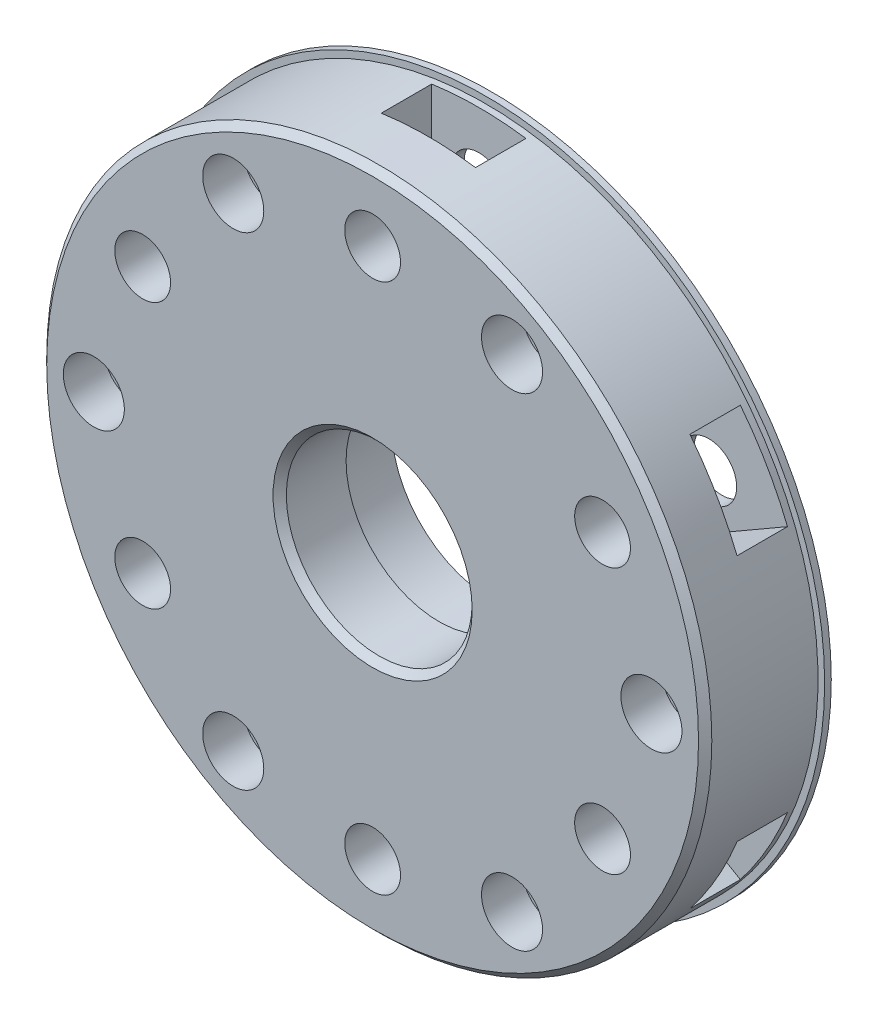
SolidWorks part; units mm, degrees
material "ABS"
ref_plane "Front Plane" through (0, 0, 0) normal (0, 0, 1) x (1, 0, 0)
ref_plane "Top Plane" through (0, 0, 0) normal (0, 1, 0) x (1, 0, 0)
ref_plane "Right Plane" through (0, 0, 0) normal (1, 0, 0) x (0, 0, -1)
sketch "Output Master Sketch" plane through (0, 0, 0) normal (0, 0, 1) x (1, 0, 0)
  circle A0 centre (0, 0) radius 21 construction
  circle A1 centre (21, 0) radius 3.05 construction
  circle A2 centre (10.5, -18.1865) radius 3.05 construction
  circle A3 centre (-10.5, -18.1865) radius 3.05 construction
  circle A4 centre (-21, 0) radius 3.05 construction
  circle A5 centre (-10.5, 18.1865) radius 3.05 construction
  circle A6 centre (10.5, 18.1865) radius 3.05 construction
  circle A7 centre (0, 0) radius 25.05
  point P17 (0, 0)
extrude "Boss-Extrude1" add sketch "Output Master Sketch" along normal blind 9
sketch "Sketch4" plane through (0, 0, 0) normal (0, 0, 1) x (1, 0, 0)
  circle A0 centre (21, 0) radius 3.05
  circle A1 centre (21, 0) radius 3.05 construction
  circle A2 centre (10.5, -18.1865) radius 3.05
  circle A3 centre (-10.5, -18.1865) radius 3.05
  circle A4 centre (-21, 0) radius 3.05
  circle A5 centre (-10.5, 18.1865) radius 3.05
  circle A6 centre (10.5, 18.1865) radius 3.05
  point P17 (0, 0)
  dimension "D1" = 6
extrude "Cut-Extrude1" cut sketch "Sketch4" along normal blind 4
sketch "Sketch5" plane through (0, 0, 0) normal (0, 0, -1) x (-1, 0, 0)
  circle A0 centre (0, 0) radius 25.05
  circle A1 centre (0, 0) radius 25.55
  circle A2 centre (0, 0) radius 25.05 construction
  dimension "D1" = 0.5
extrude "Boss-Extrude2" add sketch "Sketch5" against normal blind 0.5
sketch "Sketch6" plane through (0, 0, 0) normal (0, 0, -1) x (-1, 0, 0)
  circle A0 centre (-21, 0) radius 1.55
  circle A1 centre (-10.5, 18.1865) radius 1.55
  circle A2 centre (10.5, 18.1865) radius 1.55
  circle A3 centre (21, 0) radius 1.55
  circle A4 centre (10.5, -18.1865) radius 1.55
  circle A5 centre (-10.5, -18.1865) radius 1.55
  point P15 (0, 0)
  dimension "D1" = 3.1
  dimension "D2" = 6
extrude "Cut-Extrude2" cut sketch "Sketch6" against normal through all
sketch "Sketch7" plane through (0, 0, 9) normal (0, 0, 1) x (1, 0, 0)
  circle A0 centre (-21, 0) radius 2.3
  circle A1 centre (-10.5, 18.1865) radius 2.3
  circle A2 centre (10.5, 18.1865) radius 2.3
  circle A3 centre (21, 0) radius 2.3
  circle A4 centre (10.5, -18.1865) radius 2.3
  circle A5 centre (-10.5, -18.1865) radius 2.3
  point P16 (0, 0)
  dimension "D1" = 4.6
  dimension "D2" = 6
extrude "Cut-Extrude3" cut sketch "Sketch7" against normal blind 3.1
chamfer "Chamfer1" distance 0.5 angle 45 1 edges at (25.05, 0, 9)
sketch "Sketch8" plane through (0, 0, 0) normal (0, 0, -1) x (-1, 0, 0)
  circle A0 centre (0, 0) radius 7
  dimension "D1" = 14
extrude "Cut-Extrude4" cut sketch "Sketch8" against normal blind 10
sketch "Sketch9" plane through (0, 0, 0) normal (0, 0, -1) x (-1, 0, 0)
  circle A0 centre (0, 0) radius 7.575
  dimension "D1" = 15.15
extrude "Cut-Extrude5" cut sketch "Sketch9" against normal blind 4
sketch "Sketch10" plane through (0, 0, 9) normal (0, 0, 1) x (1, 0, 0)
  line L1 (0, 20) -> (-17.3205, 10) construction
  line L2 (-17.3205, 10) -> (-17.3205, -10) construction
  line L3 (-17.3205, -10) -> (0, -20) construction
  line L4 (0, -20) -> (17.3205, -10) construction
  line L5 (17.3205, -10) -> (17.3205, 10) construction
  line L6 (17.3205, 10) -> (0, 20) construction
  circle A0 centre (0, 0) radius 20 construction
  circle A1 centre (0, 20) radius 2.1
  circle A2 centre (17.3205, 10) radius 2.1
  circle A3 centre (17.3205, -10) radius 2.1
  circle A4 centre (0, -20) radius 2.1
  circle A5 centre (-17.3205, -10) radius 2.1
  circle A6 centre (-17.3205, 10) radius 2.1
  point P22 (0, 0)
  dimension "D1" = 40
  dimension "D2" = 4.2
  dimension "D3" = 6
extrude "M4 Thru" cut sketch "Sketch10" against normal through all
chamfer "Chamfer3" distance 0.5 angle 45 1 edges at (7, 0, 9)
sketch "Sketch11" plane through (0, 0, 9) normal (0, 0, 1) x (1, 0, 0)
  line L1 (0, 24.0992) -> (-3.55, 22.0496)
  line L2 (-3.55, 22.0496) -> (-3.55, 17.9504)
  line L3 (-3.55, 17.9504) -> (0, 15.9008)
  line L4 (0, 15.9008) -> (3.55, 17.9504)
  line L5 (3.55, 17.9504) -> (3.55, 22.0496)
  line L6 (3.55, 22.0496) -> (0, 24.0992)
  circle A0 centre (0, 20) radius 3.55 construction
  dimension "D1" = 7.1
extrude "M4 Hexnut Cut" cut sketch "Sketch11" along normal blind 3.8 from offset 8 offset against normal yes
ref_plane "Plane2" through (0, 22.0496, 0) normal (0, 1, 0) x (1, 0, 0)
sketch "Sketch12" plane through (0, 22.0496, 0) normal (0, 1, 0) x (1, 0, 0)
  line L1 (-3.55, -1) -> (3.55, -1)
  line L2 (-3.55, -1) -> (-3.55, -4.8)
  line L3 (-3.55, -4.8) -> (3.55, -4.8)
  line L4 (3.55, -1) -> (3.55, -4.8)
extrude "M4 Hexnut Slot" cut sketch "Sketch12" along normal through all contours L2 L1 L4 L3
pattern_circular "M4 Hexnut Pattern" count 6 over 360 about axis through (0, 0, 0) along (0, 0, 1) of "M4 Hexnut Cut", "M4 Hexnut Slot"
